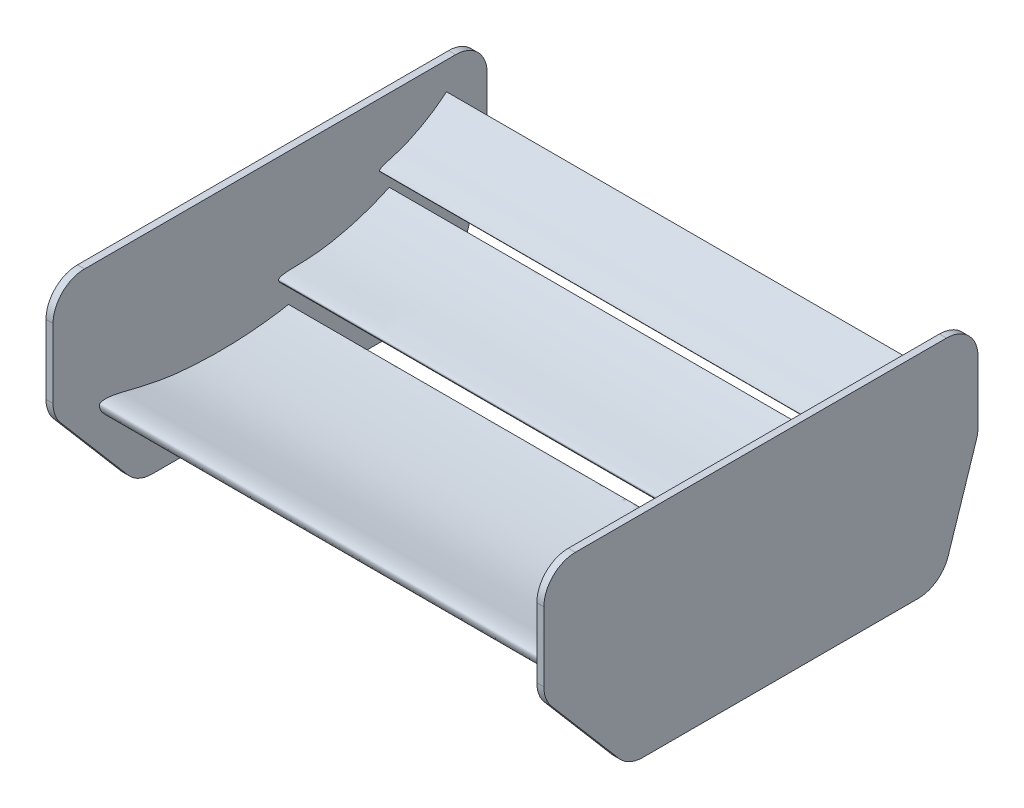
SolidWorks part; units mm, degrees
ref_plane "Front Plane" through (0, 0, 0) normal (0, 0, 1) x (1, 0, 0)
ref_plane "Top Plane" through (0, 0, 0) normal (0, 1, 0) x (1, 0, 0)
ref_plane "Right Plane" through (0, 0, 0) normal (1, 0, 0) x (0, 0, -1)
ref_plane "Soft Top Limit" through (0, 1174.6, 0) normal (0, 1, 0) x (1, 0, 0)
ref_plane "Soft Rear Limit" through (0, 0, -1192.975) normal (0, 0, 1) x (1, 0, 0)
ref_plane "Soft Right Limit" through (-501.65, 0, 0) normal (1, 0, 0) x (0, 0, -1)
ref_plane "Soft Left Limit" through (501.65, 0, 0) normal (1, 0, 0) x (0, 0, -1)
ref_plane "Soft Front Limit" through (0, 0, -165.1) normal (0, 0, 1) x (1, 0, 0)
ref_plane "Slant Limit" through (0, 528.6251, -619.2711) normal (0, -0.6492, 0.7606) x (1, 0, 0)
ref_plane "Bottom" through (0, 476.25, 0) normal (0, 1, 0) x (1, 0, 0)
ref_plane "Midplane" through (0, 0, 0) normal (1, 0, 0) x (0, 0, -1)
curve "Imported Airfoil Curve"
  spline degree 3 poles (0, 2520.0207, 6.126) (0, 2544.889, -1.81) (0, 2521.8965, 7.8839) (0, 2505.3253, 17.7145) (0, 2467.7144, 38.5723) (0, 2424.2142, 62.3813) (0, 2368.0949, 87.8078) (0, 2301.3729, 113.3478) (0, 2223.8362, 140.5377) (0, 2136.6129, 169.2441) (0, 2040.932, 199.097) (0, 1938.2341, 229.6055) (0, 1829.9414, 260.0781) (0, 1717.5266, 289.8586) (0, 1602.4273, 318.1375) (0, 1486.0259, 343.9752) (0, 1369.6902, 366.5754) (0, 1254.3666, 384.7865) (0, 1140.5393, 397.0034) (0, 1028.6357, 403.0127) (0, 919.0585, 402.9406) (0, 812.3986, 397.0375) (0, 709.2785, 385.5985) (0, 610.4299, 369.039) (0, 516.5862, 348.1086) (0, 428.5874, 323.3415) (0, 347.2653, 295.2055) (0, 273.332, 264.2656) (0, 207.4209, 231.0894) (0, 150.0337, 196.3024) (0, 101.596, 160.572) (0, 62.3674, 124.65) (0, 32.4977, 89.3959) (0, 12.0597, 55.6746) (0, 1.683, 26.6201) (0, -0.5567, 6.5526) (0, 0.5894, -3.9947) (0, 1.6947, -9.1451) (0, 2.8711, -12.4915) (0, 3.9449, -14.9776) (0, 4.8993, -16.669) (0, 5.9763, -18.2433) (0, 7.3264, -19.6365) (0, 8.8595, -20.9434) (0, 11.1868, -22.7306) (0, 14.6073, -24.7406) (0, 20.085, -27.4067) (0, 26.8353, -29.9257) (0, 44.6446, -35.1819) (0, 77.8093, -38.8998) (0, 130.2841, -38.2927) (0, 196.3018, -31.4611) (0, 276.2192, -18.4434) (0, 370.8288, 0.8611) (0, 480.7331, 24.811) (0, 605.9792, 50.0099) (0, 745.0759, 74.1542) (0, 895.4497, 95.0846) (0, 1053.6786, 110.004) (0, 1215.6439, 118.3392) (0, 1377.6893, 121.6348) (0, 1537.1174, 120.5125) (0, 1691.5141, 115.2051) (0, 1838.3121, 105.7388) (0, 1975.028, 93.0069) (0, 2099.5942, 78.4581) (0, 2210.5746, 63.1262) (0, 2306.3634, 48.0168) (0, 2387.2069, 33.7158) (0, 2449.0745, 22.0129) (0, 2499.1865, 10.4993) (0, 2520.0207, 6.126) (0, 2544.889, -1.81) (0, 2521.8965, 7.8839) knots -0.016237 -0.007308 -0.001841 0 0.001813 0.006911 0.014576 0.024172 0.035572 0.049013 0.064513 0.081849 0.100772 0.120997 0.142228 0.164173 0.186537 0.209023 0.231367 0.25332 0.274804 0.295858 0.316449 0.336531 0.356033 0.374893 0.39299 0.410197 0.426388 0.441459 0.455334 0.467938 0.479236 0.489204 0.497851 0.505194 0.511308 0.515097 0.516441 0.517273 0.51806 0.518436 0.518797 0.519154 0.519508 0.519887 0.520289 0.52116 0.522116 0.52372 0.525214 0.532575 0.542381 0.554776 0.569931 0.588005 0.609188 0.633329 0.660001 0.688743 0.718873 0.749543 0.780127 0.810209 0.839387 0.867183 0.893104 0.91676 0.937874 0.956199 0.971544 0.983763 0.992692 0.998159 1 1.001813 1.006911 1.014576 periodic
sketch "Airfoils Sketch" plane through (0, 0, 0) normal (1, 0, 0) x (0, 0, -1)
  line L0 (165.1, 1174.6) -> (165.1, 1060.6753) construction
  line L1 (165.1, 1060.6753) -> (663.9798, 476.25) construction
  line L2 (663.9798, 476.25) -> (1192.975, 476.25) construction
  line L3 (1192.975, 476.25) -> (1192.975, 1174.6) construction
  line L4 (1192.975, 1174.6) -> (165.1, 1174.6) construction
  line L5 (509.9361, 1174.6) -> (-509.9361, 1174.6) construction
  line L6 (165.1, 67.0076) -> (165.1, -67.0076) construction
  line L7 (364.7288, 826.8151) -> (873.8134, 230.4351) construction
  line L8 (279.3831, 476.25) -> (-279.3831, 476.25) construction
  line L9 (1192.975, 353.2696) -> (1192.975, -353.2696) construction
  line L10 (396.2703, 479.5603) -> (427.0731, 1361.6397) construction
  line L11 (777.4028, 476.7058) -> (807.4764, 1337.9008) construction
  line L12 (792.4396, 907.3033) -> (411.6717, 920.6) construction
  line L13 (284.6717, 920.6) -> (1192.975, 920.6) construction
  line L14 (759.51, 1016.4757) -> (786.1872, 900.9243) construction
  line L15 (982.1246, 1068.4473) -> (1009.0546, 951.8003) construction
  line L16 (995.5896, 1010.1238) -> (772.8486, 958.7) construction
  line L17 (252.1486, 958.7) -> (1192.975, 958.7) construction
  line L18 (956.518, 1084.9199) -> (996.2047, 1010.2801) construction
  line L19 (1097.7834, 1143.8587) -> (1125.0862, 1092.5095) construction
  line L20 (1110.9226, 1119.1475) -> (976.3614, 1047.6) construction
  line L21 (176.2614, 1047.6) -> (1192.975, 1047.6) construction
  spline S0 degree 3 poles (789.4107, 906.4963) (793.1825, 907.5474) (789.6821, 906.2223) (787.1434, 904.841) (781.3896, 901.924) (774.7366, 898.5973) (766.1831, 895.0985) (756.0396, 891.6416) (744.2659, 887.9977) (731.0318, 884.1804) (716.5236, 880.2383) (700.9599, 876.2371) (684.5577, 872.2723) (667.5416, 868.4342) (650.1314, 864.8362) (632.5396, 861.6114) (614.9757, 858.8714) (597.5879, 856.7837) (580.4578, 855.5862) (563.6506, 855.3085) (547.226, 855.9294) (531.2712, 857.4081) (515.8777, 859.6968) (501.153, 862.7294) (487.2029, 866.3892) (474.1503, 870.5916) (462.1172, 875.2618) (451.2073, 880.3111) (441.5123, 885.651) (433.1039, 891.1849) (426.0423, 896.8104) (420.3622, 902.4133) (416.0811, 907.864) (413.2053, 913.0324) (411.8117, 917.4453) (411.5877, 920.4658) (411.8182, 922.0404) (412.0126, 922.8062) (412.2075, 923.3013) (412.3823, 923.668) (412.5348, 923.9162) (412.705, 924.1462) (412.9151, 924.3475) (413.1522, 924.5349) (413.511, 924.7898) (414.0349, 925.072) (414.8708, 925.4412) (415.8967, 925.7812) (418.5955, 926.4699) (423.5874, 926.8425) (431.4497, 926.4594) (441.3073, 925.0678) (453.214, 922.6716) (467.288, 919.2512) (483.6287, 915.0493) (502.2621, 910.5748) (522.9775, 906.1813) (545.4012, 902.2068) (569.0358, 899.0895) (593.2671, 896.9383) (617.5384, 895.5421) (641.4421, 894.8227) (664.6148, 894.7587) (686.6718, 895.3603) (707.2356, 896.5076) (725.9884, 897.9948) (742.7091, 899.6751) (757.1514, 901.4066) (769.349, 903.1002) (778.6878, 904.5099) (786.2634, 905.9567) (789.4107, 906.4963) (793.1825, 907.5474) (789.6821, 906.2223) knots -0.016237 -0.007308 -0.001841 0 0.001813 0.006911 0.014576 0.024172 0.035572 0.049013 0.064513 0.081849 0.100772 0.120997 0.142228 0.164173 0.186537 0.209023 0.231367 0.25332 0.274804 0.295858 0.316449 0.336531 0.356033 0.374893 0.39299 0.410197 0.426388 0.441459 0.455334 0.467938 0.479236 0.489204 0.497851 0.505194 0.511308 0.515097 0.516441 0.517273 0.51806 0.518436 0.518797 0.519154 0.519508 0.519887 0.520289 0.52116 0.522116 0.52372 0.525214 0.532575 0.542381 0.554776 0.569931 0.588005 0.609188 0.633329 0.660001 0.688743 0.718873 0.749543 0.780127 0.810209 0.839387 0.867183 0.893104 0.91676 0.937874 0.956199 0.971544 0.983763 0.992692 0.998159 1 1.001813 1.006911 1.014576 only from (792.4396, 907.3033) to (792.4396, 907.3033)
  spline S1 degree 3 poles (993.9595, 1009.1857) (995.9823, 1010.3806) (994.1593, 1009.0691) (992.9025, 1007.8744) (990.0209, 1005.2902) (986.6817, 1002.3291) (982.2678, 998.973) (976.9259, 995.3944) (970.6683, 991.4542) (963.5912, 987.1867) (955.795, 982.6491) (947.3963, 977.9132) (938.5061, 973.0683) (929.2403, 968.2014) (919.7089, 963.4125) (910.0142, 958.8117) (900.2605, 954.4962) (890.5075, 950.5861) (880.7656, 947.232) (871.068, 944.461) (861.4526, 942.2702) (851.9763, 940.6495) (842.6995, 939.5855) (833.6948, 939.0564) (825.0416, 939.0112) (816.8243, 939.4197) (809.1252, 940.2577) (802.0182, 941.4899) (795.5701, 943.0791) (789.8377, 944.9806) (784.8715, 947.1442) (780.7094, 949.5094) (777.3819, 952.0035) (774.9126, 954.5523) (773.4196, 956.8934) (772.8208, 958.6092) (772.7098, 959.5575) (772.7035, 960.0316) (772.7397, 960.3488) (772.784, 960.5884) (772.8338, 960.7559) (772.8968, 960.9157) (772.9873, 961.065) (773.0956, 961.2104) (773.2639, 961.4138) (773.5237, 961.6588) (773.9509, 962.0025) (774.4926, 962.3589) (775.9498, 963.1771) (778.785, 964.1683) (783.4011, 965.1672) (789.3303, 965.8915) (796.603, 966.3518) (805.2908, 966.555) (815.4137, 966.6574) (826.9076, 966.9578) (839.5956, 967.6284) (853.2086, 968.8071) (867.3902, 970.6707) (881.7676, 973.1869) (896.0511, 976.1469) (910.0163, 979.442) (923.4561, 983.0034) (936.1459, 986.7774) (947.8856, 990.6356) (958.5229, 994.4097) (967.9526, 997.9801) (976.0538, 1001.2264) (982.86, 1004.1021) (988.0535, 1006.3694) (992.2193, 1008.3843) (993.9595, 1009.1857) (995.9823, 1010.3806) (994.1593, 1009.0691) knots -0.016237 -0.007308 -0.001841 0 0.001813 0.006911 0.014576 0.024172 0.035572 0.049013 0.064513 0.081849 0.100772 0.120997 0.142228 0.164173 0.186537 0.209023 0.231367 0.25332 0.274804 0.295858 0.316449 0.336531 0.356033 0.374893 0.39299 0.410197 0.426388 0.441459 0.455334 0.467938 0.479236 0.489204 0.497851 0.505194 0.511308 0.515097 0.516441 0.517273 0.51806 0.518436 0.518797 0.519154 0.519508 0.519887 0.520289 0.52116 0.522116 0.52372 0.525214 0.532575 0.542381 0.554776 0.569931 0.588005 0.609188 0.633329 0.660001 0.688743 0.718873 0.749543 0.780127 0.810209 0.839387 0.867183 0.893104 0.91676 0.937874 0.956199 0.971544 0.983763 0.992692 0.998159 1 1.001813 1.006911 1.014576 only from (995.5896, 1010.1238) to (995.5896, 1010.1238)
  spline S2 degree 3 poles (1110.0347, 1118.2621) (1111.1311, 1119.3806) (1110.1835, 1118.2215) (1109.5804, 1117.2353) (1108.1706, 1115.074) (1106.5313, 1112.591) (1104.268, 1109.6683) (1101.4456, 1106.4421) (1098.0958, 1102.8251) (1094.2749, 1098.8559) (1090.0375, 1094.5887) (1085.4463, 1090.0899) (1080.5574, 1085.436) (1075.4304, 1080.7032) (1070.119, 1075.9748) (1064.67, 1071.3393) (1059.1336, 1066.8774) (1053.5279, 1062.6766) (1047.8333, 1058.8358) (1042.0667, 1055.3782) (1036.2529, 1052.3083) (1030.4302, 1049.6296) (1024.64, 1047.3437) (1018.9327, 1045.4493) (1013.3683, 1043.9271) (1008.0063, 1042.7723) (1002.9038, 1041.9835) (998.1147, 1041.5506) (993.6882, 1041.4614) (989.6687, 1041.6968) (986.0974, 1042.2332) (983.0092, 1043.038) (980.436, 1044.07) (978.4061, 1045.2852) (977.0408, 1046.5352) (976.3591, 1047.5367) (976.124, 1048.1283) (976.0382, 1048.4324) (976.0067, 1048.6429) (975.9939, 1048.8049) (975.9971, 1048.9214) (976.0101, 1049.0351) (976.0426, 1049.1469) (976.0873, 1049.2592) (976.1606, 1049.4192) (976.2856, 1049.6218) (976.5013, 1049.9169) (976.7887, 1050.2398) (977.5859, 1051.0181) (979.2406, 1052.1456) (982.0408, 1053.5853) (985.7339, 1055.0748) (990.3377, 1056.6261) (995.8972, 1058.256) (1002.3981, 1060.0686) (1009.7478, 1062.2453) (1017.8026, 1064.8664) (1026.3653, 1067.9743) (1035.176, 1071.6213) (1044.0002, 1075.7224) (1052.6873, 1080.093) (1061.1116, 1084.6246) (1069.1517, 1089.2369) (1076.6721, 1093.8567) (1083.5662, 1098.3669) (1089.7649, 1102.6327) (1095.2211, 1106.5589) (1099.8777, 1110.0472) (1103.7644, 1113.0733) (1106.7175, 1115.4295) (1109.0524, 1117.4458) (1110.0347, 1118.2621) (1111.1311, 1119.3806) (1110.1835, 1118.2215) knots -0.016237 -0.007308 -0.001841 0 0.001813 0.006911 0.014576 0.024172 0.035572 0.049013 0.064513 0.081849 0.100772 0.120997 0.142228 0.164173 0.186537 0.209023 0.231367 0.25332 0.274804 0.295858 0.316449 0.336531 0.356033 0.374893 0.39299 0.410197 0.426388 0.441459 0.455334 0.467938 0.479236 0.489204 0.497851 0.505194 0.511308 0.515097 0.516441 0.517273 0.51806 0.518436 0.518797 0.519154 0.519508 0.519887 0.520289 0.52116 0.522116 0.52372 0.525214 0.532575 0.542381 0.554776 0.569931 0.588005 0.609188 0.633329 0.660001 0.688743 0.718873 0.749543 0.780127 0.810209 0.839387 0.867183 0.893104 0.91676 0.937874 0.956199 0.971544 0.983763 0.992692 0.998159 1 1.001813 1.006911 1.014576 only from (1110.9226, 1119.1475) to (1110.9226, 1119.1475)
  point P36 (0, 0)
  point P38 (0, 0)
  dimension "D1" = 381
  dimension "D2" = 254
  dimension "D3" = 2
  dimension "D4" = 127
  dimension "D5" = 228.6
  dimension "D6" = 215.9
  dimension "D7" = 13
  dimension "D8" = 520.7
  dimension "D9" = 152.4
  dimension "D10" = 127
  dimension "D11" = 28
  dimension "D12" = 800.1
extrude "Extruded Airfoils" add sketch "Airfoils Sketch" along normal offset from surface (487.45 mm away) 14.2 up to plane "Soft Left Limit"
sketch "Endplate Sketch" plane through (501.65, 0, 0) normal (1, 0, 0) x (0, 0, -1)
  line L6 (381.6529, 1174.6) -> (1129.475, 1174.6)
  line L7 (1192.975, 1174.6) -> (165.1, 1174.6) construction
  line L8 (1192.975, 1111.1) -> (1192.975, 986.6717)
  line L9 (1192.975, 476.25) -> (1192.975, 1174.6) construction
  line L11 (1189.8464, 966.9854) -> (1132.8969, 792.34)
  line L12 (1072.5255, 748.5263) -> (517.7681, 748.5263)
  line L19 (469.4715, 770.7991) -> (333.3562, 930.2547)
  line L26 (318.1529, 971.4819) -> (318.1529, 1111.1)
  line L28 (165.1, 1060.6753) -> (663.9798, 476.25) construction
  arc A12 (1129.475, 1174.6) -> (1192.975, 1111.1) centre (1129.475, 1111.1) cw
  arc A13 (1192.975, 986.6717) -> (1189.8464, 966.9854) centre (1129.475, 986.6717) cw
  arc A14 (1132.8969, 792.34) -> (1072.5255, 748.5263) centre (1072.5255, 812.0263) cw
  arc A15 (517.7681, 748.5263) -> (469.4715, 770.7991) centre (517.7681, 812.0263) cw
  arc A16 (333.3562, 930.2547) -> (318.1529, 971.4819) centre (381.6529, 971.4819) cw
  arc A17 (381.6529, 1174.6) -> (318.1529, 1111.1) centre (381.6529, 1111.1) ccw
  point P9 (1192.975, 976.5799)
  point P11 (303.1653, 982.8381)
  point P16 (1192.975, 1174.6)
  point P19 (1192.975, 976.5799)
  point P29 (318.1529, 1174.6)
  dimension "D1" = 63.5
extrude "Extruded Endplate" add sketch "Endplate Sketch" against normal up to surface (14.2 mm away)
mirror "Mirror" about plane through (0, 0, 0) normal (1, 0, 0) of bodies 106
